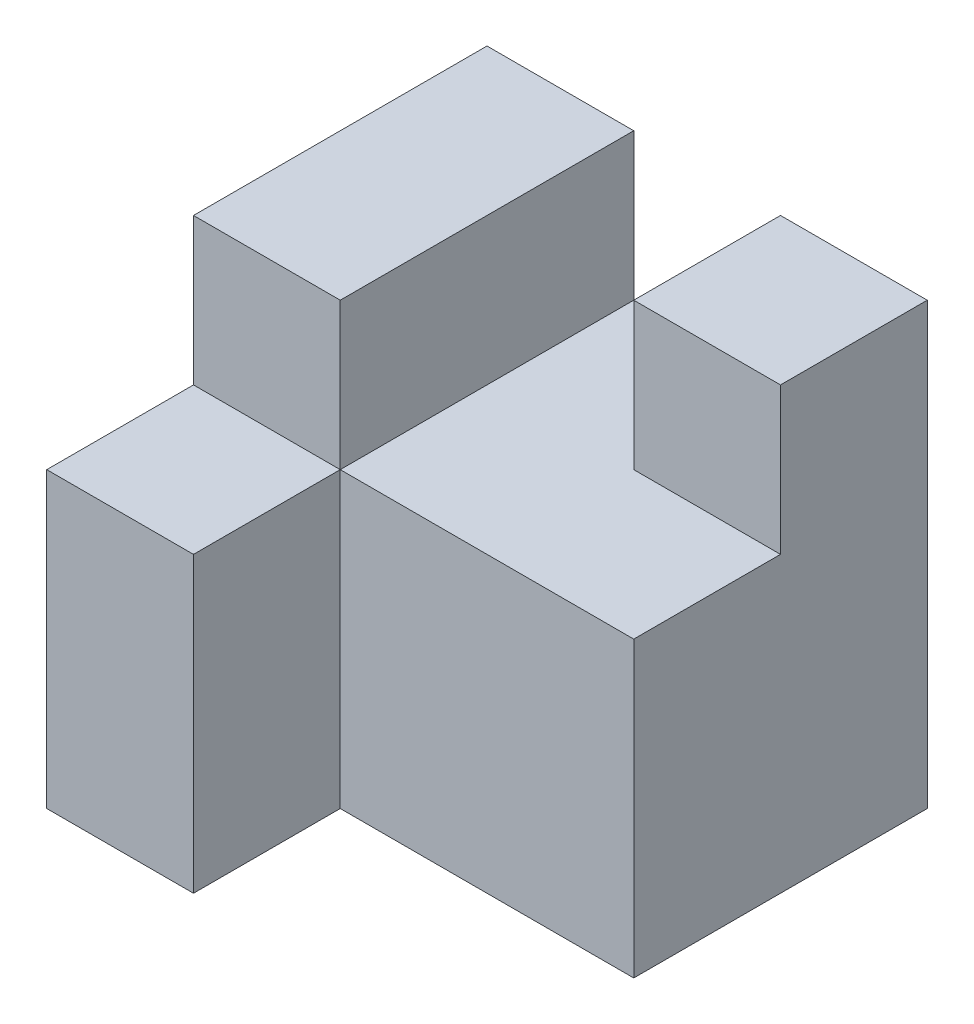
SolidWorks part; units mm, degrees
ref_plane "前基準面" through (0, 0, 0) normal (0, 0, 1) x (1, 0, 0)
ref_plane "上基準面" through (0, 0, 0) normal (0, 1, 0) x (1, 0, 0)
ref_plane "右基準面" through (0, 0, 0) normal (1, 0, 0) x (0, 0, -1)
sketch "草圖1" plane through (0, 0, 0) normal (0, 0, 1) x (1, 0, 0)
  line L1 (0, 0) -> (30, 0)
  line L2 (0, 0) -> (0, 30)
  line L3 (0, 30) -> (30, 30)
  line L4 (30, 0) -> (30, 30)
  dimension "D1" = 30
  dimension "D2" = 30
extrude "填料-伸1" add sketch "草圖1" against normal blind 30
sketch "草圖5" plane through (0, 0, 0) normal (0, 0, 1) x (1, 0, 0)
  line L0 (10, 30) -> (10, 20)
  line L1 (10, 20) -> (20, 20)
  line L2 (20, 20) -> (20, 30)
  line L4 (0, 30) -> (0, 0)
  line L5 (0, 0) -> (30, 0)
  line L6 (30, 0) -> (30, 30)
  line L7 (30, 30) -> (0, 30)
  line L8 (0, 30) -> (0, 0)
  line L9 (0, 0) -> (30, 0)
  line L10 (30, 0) -> (30, 30)
  line L11 (30, 30) -> (0, 30)
  line M11 (30, 30) -> (0, 30)
  dimension "D2" = 10
  dimension "D3" = 10
  dimension "D4" = 10
  dimension "D5" = 10
  dimension "D1" = 0
extrude "除料-伸長4" cut sketch "草圖5" against normal through all contours L1 L2 L0 M11
sketch "草圖7" plane through (0, 30, 0) normal (0, 1, 0) x (1, 0, 0)
  line L0 (30, 0) -> (20, 0) construction
  line L1 (30, 0) -> (10, 0)
  line L2 (30, 0) -> (30, 10)
  line L3 (30, 10) -> (10, 10)
  line L4 (10, 0) -> (10, 10)
  line L5 (30, 30) -> (30, 0) construction
  point P8 (20, 10)
  dimension "D1" = 10
  dimension "D2" = 20
extrude "除料-伸長5" cut sketch "草圖7" against normal through all
sketch "草圖9" plane through (30, 0, 0) normal (1, 0, 0) x (0, 0, -1)
  line L1 (10, 30) -> (0, 30)
  line L2 (10, 30) -> (10, 20)
  line L3 (10, 20) -> (0, 20)
  line L4 (0, 30) -> (0, 20)
  dimension "D1" = 10
  dimension "D2" = 10
extrude "除料-伸長6" cut sketch "草圖9" against normal through all
sketch "草圖10" plane through (30, 0, 0) normal (1, 0, 0) x (0, 0, -1)
  line L1 (10, 30) -> (20, 30)
  line L2 (10, 30) -> (10, 20)
  line L3 (10, 20) -> (20, 20)
  line L4 (20, 30) -> (20, 20)
  dimension "D1" = 10
  dimension "D2" = 10
extrude "除料-伸長7" cut sketch "草圖10" against normal blind 15
